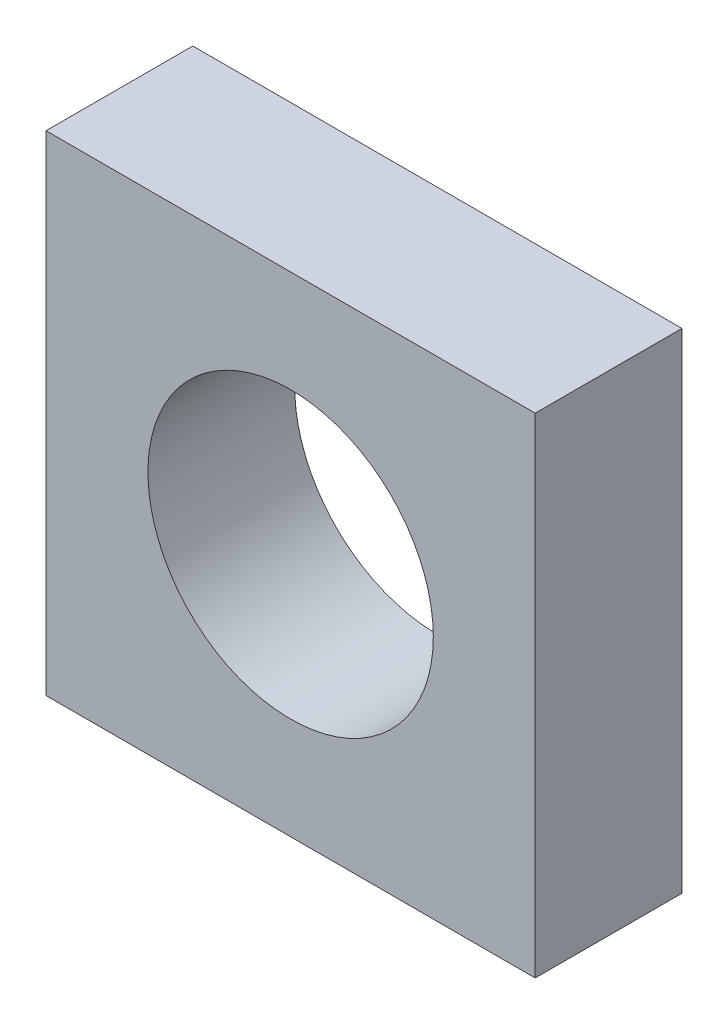
SolidWorks part; units mm, degrees
ref_plane "Piano frontale" through (0, 0, 0) normal (0, 0, 1) x (1, 0, 0)
ref_plane "Piano superiore" through (0, 0, 0) normal (0, 1, 0) x (1, 0, 0)
ref_plane "Piano destro" through (0, 0, 0) normal (1, 0, 0) x (0, 0, -1)
sketch "Schizzo1" plane through (0, 0, 0) normal (0, 0, 1) x (1, 0, 0)
  line L1 (-3, -3) -> (3, -3)
  line L2 (-3, -3) -> (-3, 3)
  line L3 (-3, 3) -> (3, 3)
  line L4 (3, -3) -> (3, 3)
  line L5 (-3, -3) -> (3, 3) construction
  line L6 (-3, 3) -> (3, -3) construction
  circle A0 centre (0, 0) radius 1.75
  point P0 (0, 0)
  dimension "D2" = 3.5
  dimension "D1" = 6
extrude "Estrusione-Estrusione1" add sketch "Schizzo1" along normal mid plane 1.8
